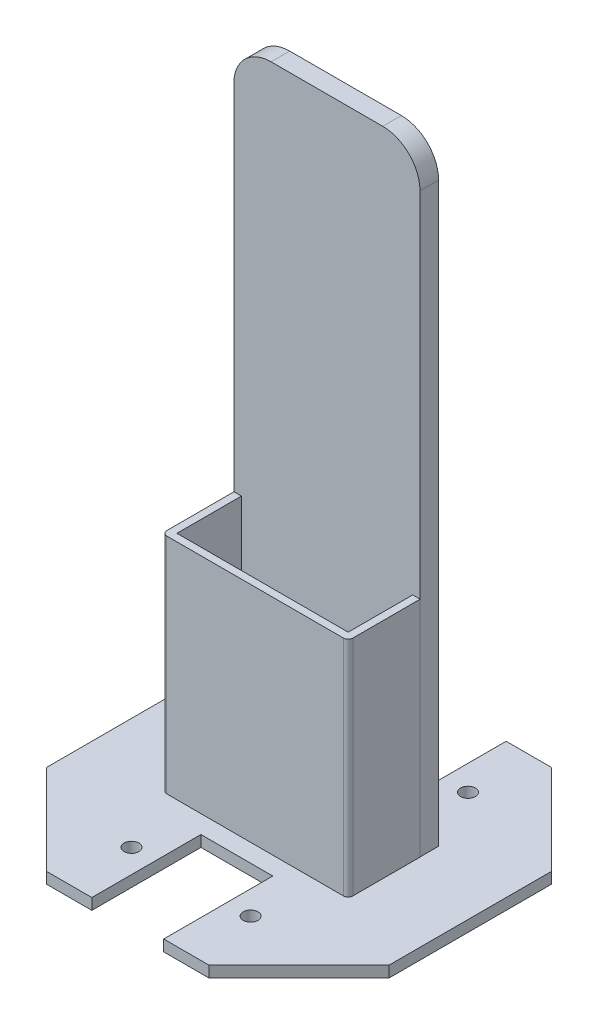
SolidWorks part; units mm, degrees
ref_plane "Alzado" through (0, 0, 0) normal (0, 0, 1) x (1, 0, 0)
ref_plane "Planta" through (0, 0, 0) normal (0, 1, 0) x (1, 0, 0)
ref_plane "Vista lateral" through (0, 0, 0) normal (1, 0, 0) x (0, 0, -1)
sketch "Croquis1" plane through (0, 0, 0) normal (0, 1, 0) x (1, 0, 0)
  line L0 (-46, 21.8057) -> (-46, -21.8057)
  line L1 (-46, -21.8057) -> (-21.8057, -46)
  line L2 (-21.8057, -46) -> (21.8057, -46)
  line L3 (21.8057, -46) -> (46, -21.8057)
  line L4 (46, -21.8057) -> (46, 21.8057)
  line L5 (46, 21.8057) -> (21.8057, 46)
  line L6 (21.8057, 46) -> (-21.8057, 46)
  line L7 (-21.8057, 46) -> (-46, 21.8057)
  line L8 (0, -46) -> (0, 46) construction
  line L9 (-46, 0) -> (46, 0) construction
  point P12 (0, 0)
  dimension "D1" = 92
  dimension "D2" = 92
  dimension "D3" = 21.8057
extrude "Saliente-Extruir1" add sketch "Croquis1" along normal blind 3
sketch "Croquis2" plane through (0, 3, 0) normal (0, 1, 0) x (1, 0, 0)
  line L0 (-25, 12.5) -> (25, 12.5)
  line L1 (25, 12.5) -> (25, -12.5)
  line L2 (25, -12.5) -> (-25, -12.5)
  line L3 (-25, -12.5) -> (-25, 12.5)
  line L4 (0, 0) -> (0, 19.0136) construction
  line L5 (0, 0) -> (0, -17.9748) construction
  line L6 (0, 0) -> (-29.6559, 0) construction
  line L7 (0, 0) -> (34.0531, 0) construction
  dimension "D1" = 25
  dimension "D2" = 50
  dimension "D3" = 12.5
  dimension "D4" = 34.0531
  dimension "D5" = 25
extrude "Saliente-Extruir2" add sketch "Croquis2" along normal blind 165
sketch "Croquis5" plane through (-25, 0, 0) normal (-1, 0, 0) x (0, 0, 1)
  line L0 (-12.5, 168) -> (12.5, 168) construction
  line L1 (-7.5, 168) -> (12.5, 168)
  line L2 (-7.5, 168) -> (-7.5, 3)
  line L3 (-7.5, 3) -> (12.5, 3)
  line L4 (12.5, 168) -> (12.5, 3)
  line L5 (-12.5, 168) -> (-12.5, 3) construction
  line L6 (-14.2464, 137.5367) -> (-12.5, 137.5367)
  line L7 (-14.2464, 137.5367) -> (-14.2464, 138.1793)
  line L8 (-14.2464, 138.1793) -> (-12.5, 138.1793)
  line L9 (-12.5, 137.5367) -> (-12.5, 138.1793)
  dimension "D1" = 5
extrude "Cortar-Extruir2" cut sketch "Croquis5" against normal blind 76
ref_plane "Plano1" through (0, 0, 19.5) normal (0, 0, 1) x (1, 0, 0)
sketch "Croquis6" plane through (0, 0, 19.5) normal (0, 0, 1) x (1, 0, 0)
  line L0 (-25, 168) -> (-25, 3) construction
  line L1 (-25, 3) -> (25, 3)
  line L2 (-25, 3) -> (-25, 23)
  line L3 (-25, 23) -> (25, 23)
  line L4 (25, 3) -> (25, 23)
  line L5 (25, 168) -> (25, 3) construction
  dimension "D1" = 20
sketch "Croquis8" plane through (0, 3, -4.5772) normal (0, 1, 0) x (1, 0, 0)
  line L0 (25, 2.9228) -> (-25, 2.9228) construction
  line L1 (-24.9551, 2.9228) -> (25.0449, 2.9228)
  line L2 (-24.9551, 2.9228) -> (-24.9551, -16.4162)
  line L3 (-24.9551, -16.4162) -> (25.0449, -16.4162)
  line L4 (25.0449, 2.9228) -> (25.0449, -16.4162)
  line L5 (0.9471, 0) -> (-38.934, 0) construction
  line L6 (0.9471, 0) -> (36.4035, 0) construction
  line L7 (0.9471, 0) -> (0.9471, 22.8485) construction
  line L9 (-25, 2.9228) -> (25, 2.9228) construction
  line L10 (-25, 7.9228) -> (-25, 2.9228) construction
  line L11 (25, 2.9228) -> (25, 7.9228) construction
fillet "Redondeo1" radius 10 2 edges at (-25, 168, -10) (25, 168, -10)
extrude "Saliente-Extruir10" add sketch "Croquis8" along normal blind 60
sketch "Croquis12" plane through (0, 63, 0) normal (0, 1, 0) x (1, 0, 0)
  line L0 (25.0449, -11.839) -> (25.0449, 7.5) construction
  line L1 (-22.9551, 5.5) -> (23.0449, 5.5)
  line L2 (-22.9551, 5.5) -> (-22.9551, -9.839)
  line L3 (-22.9551, -9.839) -> (23.0449, -9.839)
  line L4 (23.0449, 5.5) -> (23.0449, -9.839)
  line L5 (-24.9551, 7.5) -> (25, 7.5) construction
  line L6 (-24.9551, -11.839) -> (25.0449, -11.839) construction
  line L7 (-24.9551, 7.5) -> (-24.9551, -11.839) construction
  dimension "D1" = 2
  dimension "D2" = 2
  dimension "D3" = 2
  dimension "D4" = 2
extrude "Cortar-Extruir6" cut sketch "Croquis12" against normal blind 60
fillet "Redondeo5" radius 1.25 2 edges at (-24.9551, 33, 11.839) (25.0449, 33, 11.839)
sketch "Croquis15" plane through (0, 0, -5.5) normal (0, 0, 1) x (1, 0, 0)
  line L0 (23.0449, 3) -> (-22.9551, 3) construction
  line L1 (23.0449, 3) -> (23.0449, 63) construction
  line L2 (-22.9551, 3) -> (-22.9551, 63) construction
  line L3 (23.0449, 63) -> (-22.9551, 63) construction
  line L4 (23.0449, 3) -> (-22.9551, 3)
  line L5 (23.0449, 3) -> (23.0449, 63)
  line L6 (-22.9551, 3) -> (-22.9551, 63)
  line L7 (23.0449, 63) -> (-22.9551, 63)
extrude "Cortar-Extruir7" cut sketch "Croquis15" against normal blind 2
sketch "Croquis16" plane through (0, 3, 0) normal (0, 1, 0) x (1, 0, 0)
  line L0 (77.5305, 0) -> (-77.5305, 0) construction
  line L1 (0, -49.6929) -> (0, 49.6929) construction
  line L4 (21.8057, 46) -> (-21.8057, 46) construction
  line L9 (-9.65, 46) -> (9.65, 46)
  line L10 (-9.65, 46) -> (-9.65, 16.7)
  line L11 (-9.65, 16.7) -> (9.65, 16.7)
  line L12 (9.65, 46) -> (9.65, 16.7)
  line L13 (-9.65, -16.7) -> (9.65, -16.7)
  line L14 (9.65, -46) -> (9.65, -16.7)
  line L15 (-9.65, -46) -> (9.65, -46)
  line L16 (-9.65, -46) -> (-9.65, -16.7)
  circle A0 centre (-17, 29) radius 2
  circle A1 centre (16.4, 29) radius 2
  circle A2 centre (-16, -29) radius 2
  circle A3 centre (16, -29) radius 2
  point P0 (-17, 29)
  point P4 (0, 0)
  point P8 (0, 0)
  point P9 (16.4, 29)
  point P10 (16, -29)
  point P11 (-16, -29)
  dimension "D9" = 4
  dimension "D10" = 4
  dimension "D11" = 4
  dimension "D12" = 4
  dimension "D13" = 29.3
  dimension "D14" = 19.3
  dimension "D1" = 29
  dimension "D2" = 17
  dimension "D3" = 29
  dimension "D4" = 16.4
  dimension "D5" = 16
  dimension "D6" = 29
  dimension "D7" = 29
  dimension "D8" = 16
  dimension "D15" = 9.65
extrude "Cortar-Extruir8" cut sketch "Croquis16" against normal blind 12
